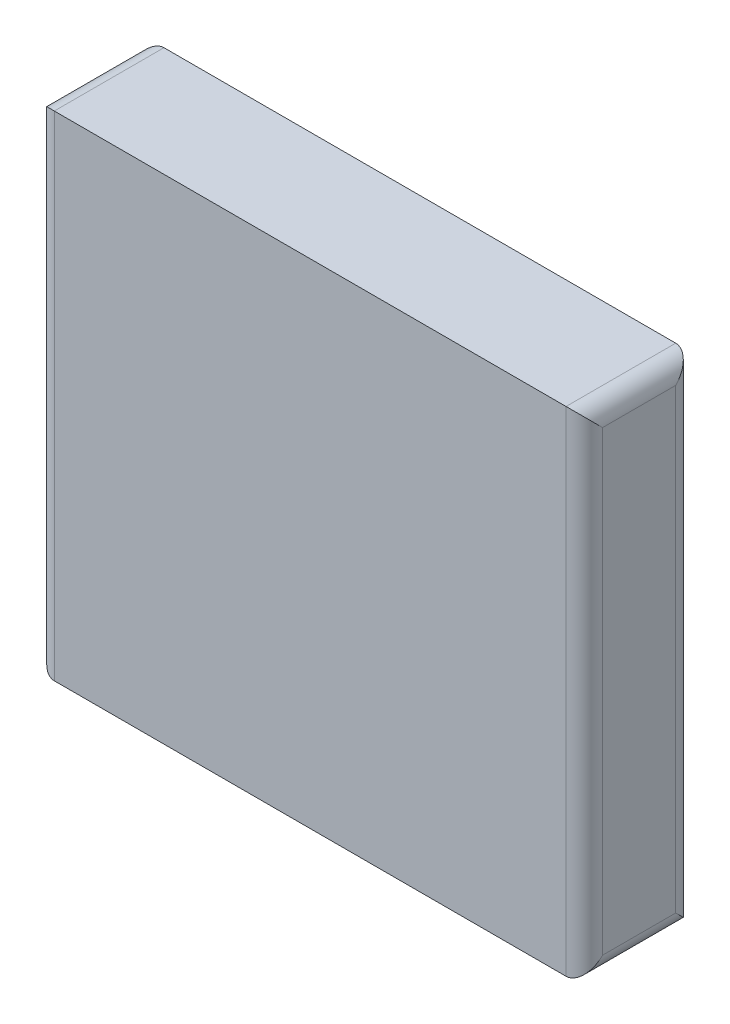
SolidWorks part; units mm, degrees
ref_plane "Plan de face" through (0, 0, 0) normal (0, 0, 1) x (1, 0, 0)
ref_plane "Plan de dessus" through (0, 0, 0) normal (0, 1, 0) x (1, 0, 0)
ref_plane "Plan de droite" through (0, 0, 0) normal (1, 0, 0) x (0, 0, -1)
sketch "Esquisse1" plane through (0, 0, 0) normal (0, 0, 1) x (1, 0, 0)
  line L1 (0, 0) -> (30, 0)
  line L2 (0, 0) -> (0, 27)
  line L3 (0, 27) -> (30, 27)
  line L4 (30, 0) -> (30, 27)
  dimension "D1" = 30
  dimension "D2" = 27
extrude "Boss.-Extru.1" add sketch "Esquisse1" along normal blind 6
fillet "Congé1" radius 1 8 edges at (0, 0, 3) (0, 13.5, 0) (0, 27, 3) (0, 13.5, 6) (30, 0, 3) (30, 13.5, 0) (30, 27, 3) (30, 13.5, 6)
